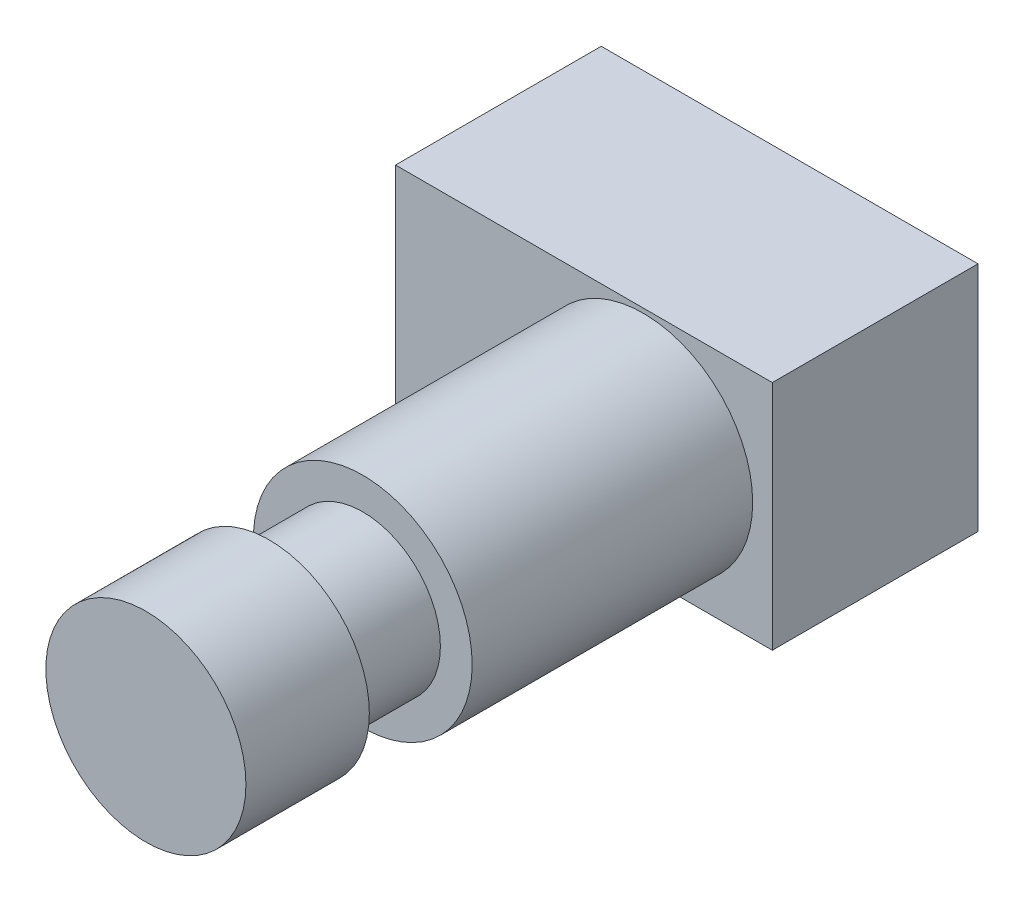
SolidWorks part; units mm, degrees
ref_plane "Alzado" through (0, 0, 0) normal (0, 0, 1) x (1, 0, 0)
ref_plane "Planta" through (0, 0, 0) normal (0, 1, 0) x (1, 0, 0)
ref_plane "Vista lateral" through (0, 0, 0) normal (1, 0, 0) x (0, 0, -1)
sketch "Croquis1" plane through (0, 0, 0) normal (0, 0, 1) x (1, 0, 0)
  circle A0 centre (0, 0) radius 5.85
  dimension "D1" = 11.7
extrude "Saliente-Extruir1" add sketch "Croquis1" along normal blind 15
sketch "Croquis2" plane through (0, 0, 15) normal (0, 0, 1) x (1, 0, 0)
  circle A0 centre (0, 0) radius 4.15
  dimension "D1" = 8.3
extrude "Saliente-Extruir2" add sketch "Croquis2" along normal blind 5
sketch "Croquis3" plane through (0, 0, 20) normal (0, 0, 1) x (1, 0, 0)
  circle A0 centre (0, 0) radius 5.35
  dimension "D1" = 10.7
extrude "Saliente-Extruir3" add sketch "Croquis3" along normal blind 6.6
sketch "Croquis4" plane through (0, 0, 0) normal (0, 0, -1) x (-1, 0, 0)
  line L0 (5.85, 0) -> (5.85, 3.9691) construction
  line L1 (13.25, -6.3131) -> (-6.9, -6.3131)
  line L2 (13.25, -6.3131) -> (13.25, 6.0869)
  line L3 (13.25, 6.0869) -> (-6.9, 6.0869)
  line L4 (-6.9, -6.3131) -> (-6.9, 6.0869)
  line L5 (13.25, -6.3131) -> (-6.9, 6.0869) construction
  line L6 (13.25, 6.0869) -> (-6.9, -6.3131) construction
  circle A0 centre (0, 0) radius 5.85 construction
  point P0 (3.175, -0.1131)
  dimension "D3" = 7.4
  dimension "D1" = 20.15
  dimension "D2" = 12.4
extrude "Saliente-Extruir4" add sketch "Croquis4" along normal blind 11
